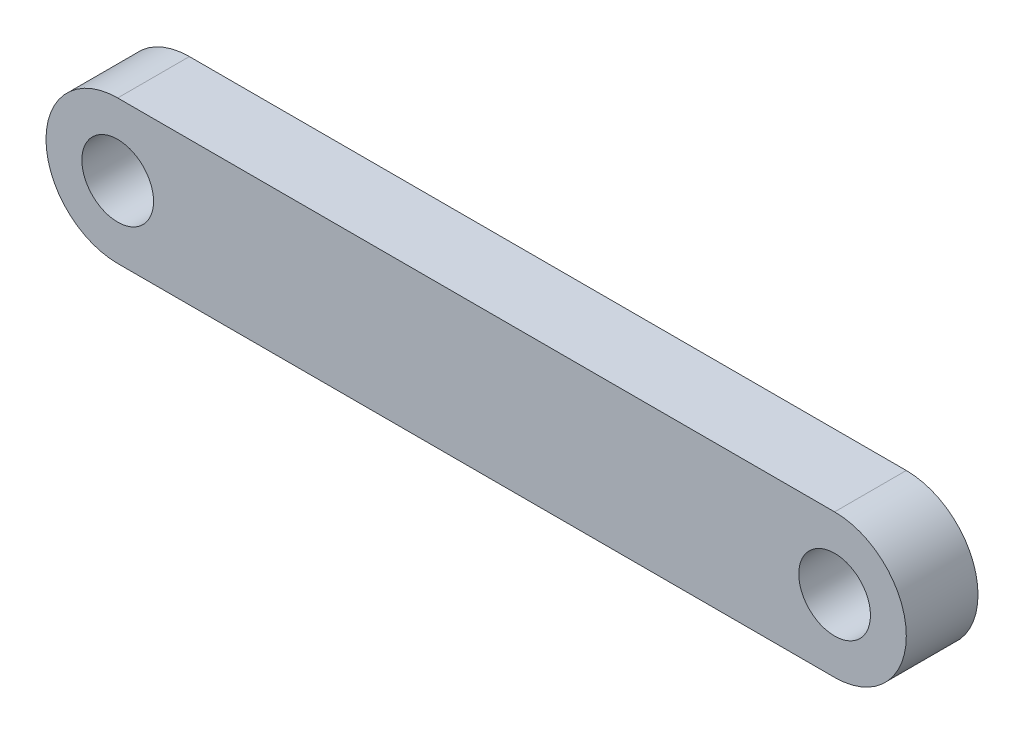
SolidWorks part; units mm, degrees
material "PMMA"
ref_plane "前视基准面" through (0, 0, 0) normal (0, 0, 1) x (1, 0, 0)
ref_plane "上视基准面" through (0, 0, 0) normal (0, 1, 0) x (1, 0, 0)
ref_plane "右视基准面" through (0, 0, 0) normal (1, 0, 0) x (0, 0, -1)
other "Configuration Table"
sketch "草图1" plane through (0, 0, 0) normal (0, 0, 1) x (1, 0, 0)
  line L0 (-15, 0) -> (15, 0) construction
  line L1 (-15, 3) -> (15, 3)
  line L2 (-15, -3) -> (15, -3)
  arc A0 (-15, 3) -> (-15, -3) centre (-15, 0) ccw
  arc A1 (15, -3) -> (15, 3) centre (15, 0) ccw
  circle A2 centre (15, 0) radius 1.5
  circle A3 centre (-15, 0) radius 1.5
  point P2 (0, 0)
  dimension "D2" = 3
  dimension "D3" = 3
  dimension "D4" = 3
  dimension "D1" = 30
extrude "凸台-拉伸1" add sketch "草图1" along normal blind 3
